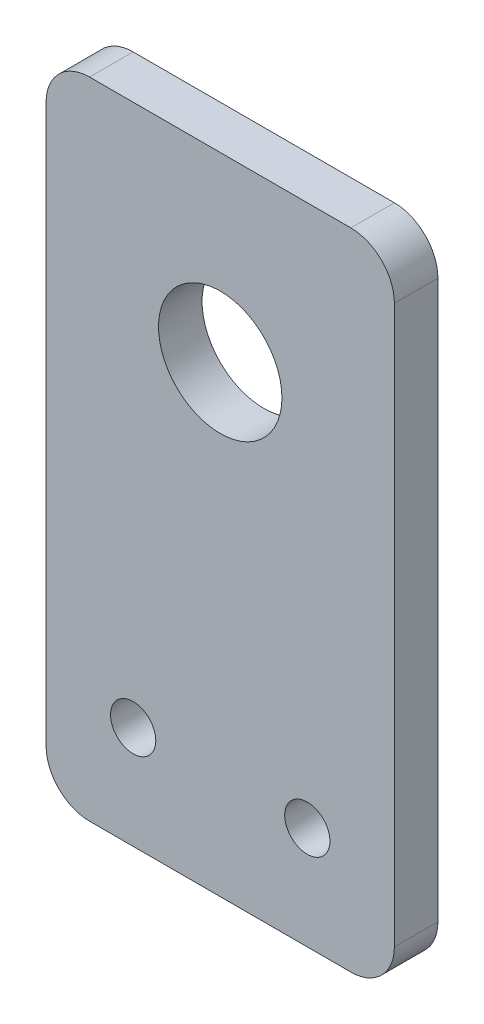
SolidWorks part; units mm, degrees
material "Acrylic (Medium-high impact)"
ref_plane "Front Plane" through (0, 0, 0) normal (0, 0, 1) x (1, 0, 0)
ref_plane "Top Plane" through (0, 0, 0) normal (0, 1, 0) x (1, 0, 0)
ref_plane "Right Plane" through (0, 0, 0) normal (1, 0, 0) x (0, 0, -1)
sketch "Sketch1" plane through (0, 0, 0) normal (0, 0, 1) x (1, 0, 0)
  line L1 (-12.7, -23.5) -> (12.7, -23.5)
  line L2 (-12.7, -23.5) -> (-12.7, 23.5)
  line L3 (-12.7, 23.5) -> (12.7, 23.5)
  line L4 (12.7, -23.5) -> (12.7, 23.5)
  line L5 (-12.7, -23.5) -> (12.7, 23.5) construction
  line L6 (-12.7, 23.5) -> (12.7, -23.5) construction
  point P0 (0, 0)
  dimension "D1" = 25.4
  dimension "D2" = 47
extrude "Boss-Extrude1" add sketch "Sketch1" along normal blind 3.175
sketch "Sketch2" plane through (0, 0, 3.175) normal (0, 0, 1) x (1, 0, 0)
  line L0 (12.7, -23.5) -> (12.7, 23.5) construction
  line L1 (12.7, 23.5) -> (-12.7, 23.5) construction
  circle A0 centre (0, 10.25) radius 4.5
  dimension "D1" = 9
  dimension "D2" = 12.7
  dimension "D3" = 13.25
extrude "Cut-Extrude1" cut sketch "Sketch2" against normal through all
ref_plane "Plane1" through (0, 0, 3.175) normal (0, 0, 1) x (1, 0, 0)
fillet "Fillet1" radius 3.175 4 edges at (-12.7, -23.5, 1.5875) (12.7, -23.5, 1.5875) (12.7, 23.5, 1.5875) (-12.7, 23.5, 1.5875)
ref_plane "Plane2" through (0, 0, 3.175) normal (0, 0, 1) x (1, 0, 0)
sketch "Sketch6" plane through (0, 0, 3.175) normal (0, 0, 1) x (1, 0, 0)
  line L0 (-12.7, 20.325) -> (-12.7, -20.325) construction
  line L1 (-9.525, -23.5) -> (9.525, -23.5) construction
  point P0 (-6.35, -16)
  point P1 (6.35, -16)
  dimension "D1" = 12.7
  dimension "D2" = 6.35
  dimension "D3" = 7.5
hole_wizard "M4x0.7 Tapped Hole1" positions "Sketch7" profile "Sketch8" tap size "M4x0.7" standard "ANSI Metric" end condition through all
sketch "Sketch7" plane through (0, 0, 3.175) normal (0, 0, 1) x (1, 0, 0)
  point P0 (-6.35, -16)
  point P3 (6.35, -16)
sketch "Sketch8" plane through (-6.35, -16, 3.175) normal (1, 0, 0) x (0, -1, 0)
  line L0 (0, 0) -> (0, 3.175)
  line L1 (0, 3.175) -> (1.65, 3.175)
  line L2 (1.65, 3.175) -> (1.65, 0)
  line L5 (1.65, 0) -> (0, 0)
  line L11 (0, -6.35) -> (0, 107.95) construction
  dimension "Thru Tap Drill Dia." = 3.3
  dimension "Thru Tap Drill Depth" = 3.175
